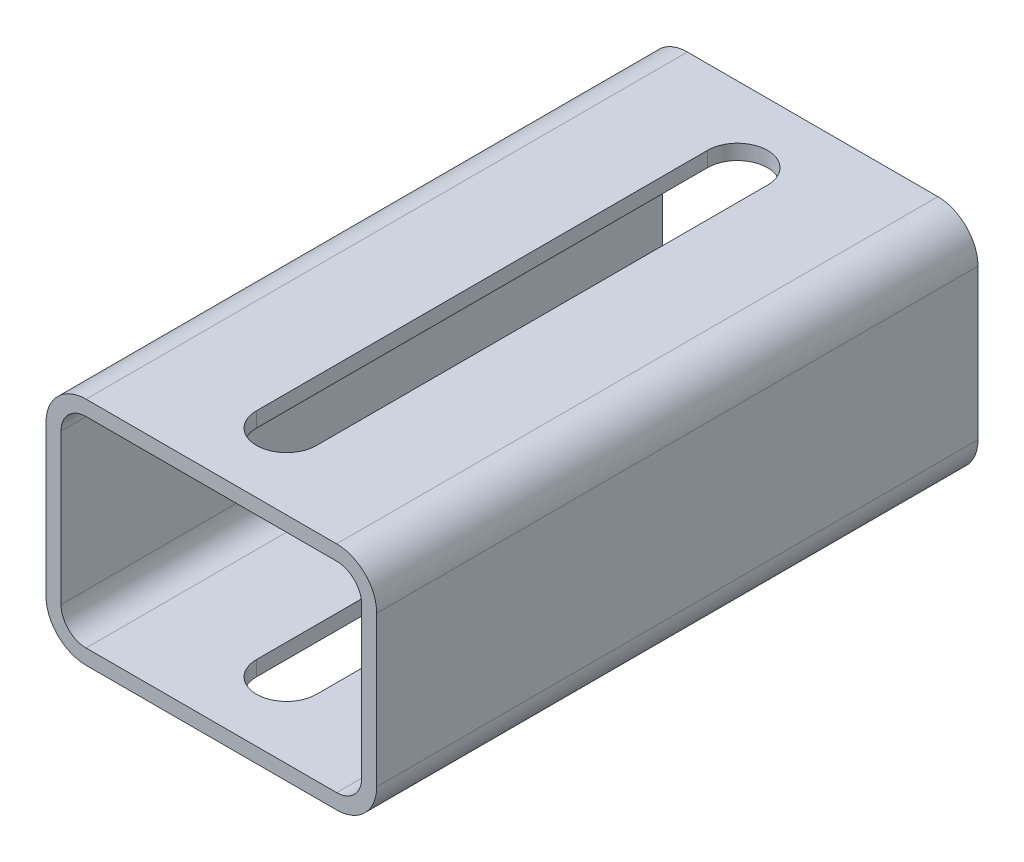
SolidWorks part; units mm, degrees
ref_plane "Front Plane" through (0, 0, 0) normal (0, 0, 1) x (1, 0, 0)
ref_plane "Top Plane" through (0, 0, 0) normal (0, 1, 0) x (1, 0, 0)
ref_plane "Right Plane" through (0, 0, 0) normal (1, 0, 0) x (0, 0, -1)
sketch "Sketch1" plane through (0, 0, 0) normal (0, 0, 1) x (1, 0, 0)
  line L1 (-25, -20) -> (25, -20)
  line L2 (-30, -15) -> (-30, 15)
  line L3 (-25, 20) -> (25, 20)
  line L4 (30, -15) -> (30, 15)
  line L5 (-30, -20) -> (30, 20) construction
  line L6 (-30, 20) -> (30, -20) construction
  arc A0 (25, 20) -> (30, 15) centre (25, 15) cw
  arc A1 (25, -20) -> (30, -15) centre (25, -15) ccw
  arc A2 (-25, -20) -> (-30, -15) centre (-25, -15) cw
  arc A3 (-30, 15) -> (-25, 20) centre (-25, 15) cw
  point P0 (0, 0)
  point P6 (0, 0)
  dimension "D3" = 5
  dimension "Height" = 40
  dimension "Length" = 60
extrude "Extrude-Thin1" add sketch "Sketch1" along normal mid plane 120 thin
sketch "Sketch2" plane through (0, 23, 0) normal (0, 1, 0) x (1, 0, 0)
  line L0 (0, 45) -> (0, -45) construction
  line L3 (6, 45) -> (6, -45)
  line L4 (-6, 45) -> (-6, -45)
  arc A2 (6, 45) -> (-6, 45) centre (0, 45) ccw
  arc A3 (-6, -45) -> (6, -45) centre (0, -45) ccw
  point P3 (0, 0)
  dimension "D2" = 6
  dimension "D1" = 90
  dimension "D3" = 45
extrude "Cut-Extrude1" cut sketch "Sketch2" against normal through all
